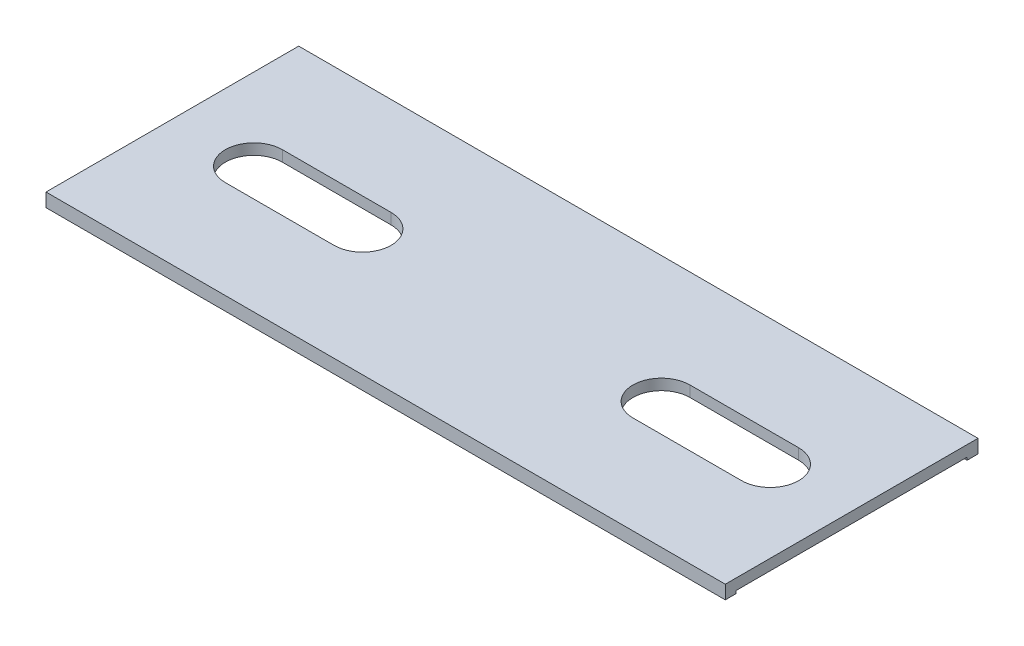
SolidWorks part; units mm, degrees
ref_plane "Front Plane" through (0, 0, 0) normal (0, 0, 1) x (1, 0, 0)
ref_plane "Top Plane" through (0, 0, 0) normal (0, 1, 0) x (1, 0, 0)
ref_plane "Right Plane" through (0, 0, 0) normal (1, 0, 0) x (0, 0, -1)
sketch "Sketch3" plane through (0, 0, 0) normal (1, 0, 0) x (0, 0, -1)
  line L0 (0, 0) -> (23.622, 0)
  line L1 (23.622, 0) -> (23.622, -1.27)
  line L2 (0, 0) -> (0, -1.27)
  line L3 (0, -1.27) -> (1.016, -1.27)
  line L4 (1.016, -1.27) -> (1.016, -1.016)
  line L5 (1.016, -1.016) -> (22.606, -1.016)
  line L6 (22.606, -1.016) -> (22.606, -1.27)
  line L7 (22.606, -1.27) -> (23.622, -1.27)
  dimension "D1" = 23.622
  dimension "D2" = 1.27
  dimension "D3" = 1.27
  dimension "D4" = 1.016
  dimension "D5" = 0.254
  dimension "D6" = 1.016
extrude "Boss-Extrude1" add sketch "Sketch3" along normal blind 63.5
sketch "Sketch4" plane through (0, 0, 0) normal (0, 1, 0) x (1, 0, 0)
  line L0 (0, 11.811) -> (7.62, 11.811) construction
  line L1 (0, 23.622) -> (0, 0) construction
  line L2 (63.5, 23.622) -> (63.5, 0) construction
  line L3 (55.88, 11.811) -> (63.5, 11.811) construction
  line L5 (7.62, 14.478) -> (17.78, 14.478)
  line L6 (7.62, 9.144) -> (17.78, 9.144)
  line L7 (45.72, 9.144) -> (55.88, 9.144)
  line L8 (45.72, 14.478) -> (55.88, 14.478)
  line L9 (17.78, 11.811) -> (43.053, 11.811) construction
  arc A0 (7.62, 14.478) -> (7.62, 9.144) centre (7.62, 11.811) ccw
  arc A1 (55.88, 9.144) -> (55.88, 14.478) centre (55.88, 11.811) ccw
  arc A2 (17.78, 9.144) -> (17.78, 14.478) centre (17.78, 11.811) ccw
  arc A3 (45.72, 14.478) -> (45.72, 9.144) centre (45.72, 11.811) ccw
  dimension "D1" = 5.334
  dimension "D2" = 5.334
  dimension "D7" = 5.334
  dimension "D8" = 5.334
  dimension "D3" = 7.62
  dimension "D4" = 7.62
  dimension "D5" = 10.16
  dimension "D6" = 10.16
extrude "Cut-Extrude1" cut sketch "Sketch4" against normal through all
